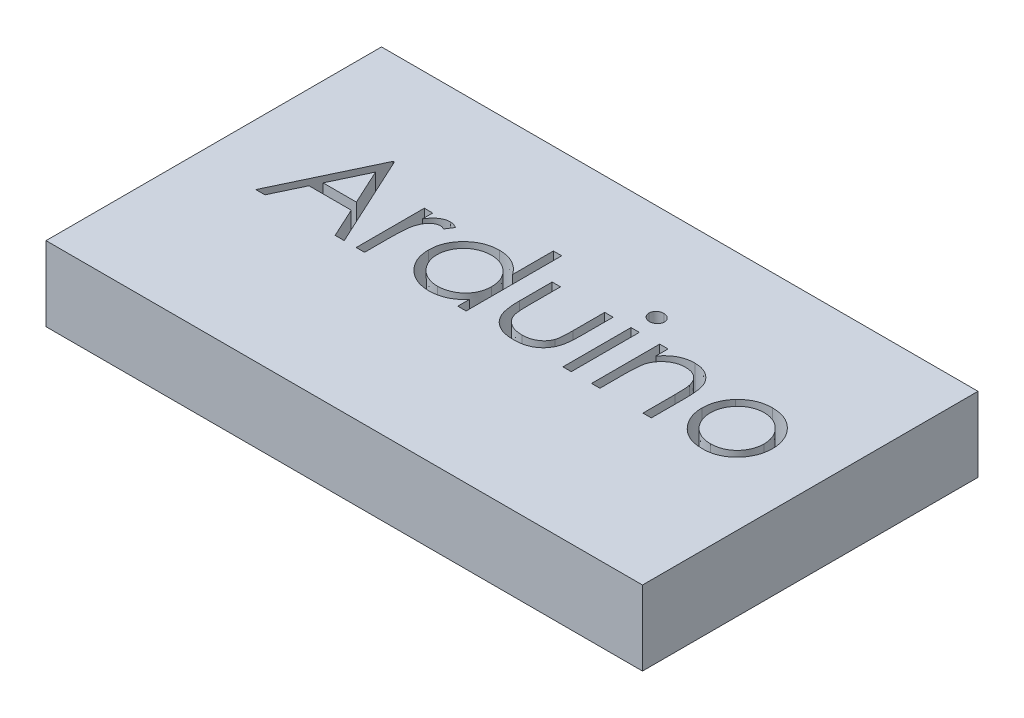
SolidWorks part; units mm, degrees
ref_plane "Front Plane" through (0, 0, 0) normal (0, 0, 1) x (1, 0, 0)
ref_plane "Top Plane" through (0, 0, 0) normal (0, 1, 0) x (1, 0, 0)
ref_plane "Right Plane" through (0, 0, 0) normal (1, 0, 0) x (0, 0, -1)
sketch "Sketch1" plane through (0, 0, 0) normal (0, 1, 0) x (1, 0, 0)
  line L1 (0, 0) -> (101.6, 0)
  line L2 (0, 0) -> (0, 57.15)
  line L3 (0, 57.15) -> (101.6, 57.15)
  line L4 (101.6, 0) -> (101.6, 57.15)
  dimension "D1" = 57.15
  dimension "D2" = 101.6
extrude "Boss-Extrude1" add sketch "Sketch1" along normal blind 12.7
sketch "Sketch2" plane through (0, 12.7, 0) normal (0, 1, 0) x (1, 0, 0)
  line L0 (0, 57.15) -> (0, 0) construction
  line L1 (101.6, 57.15) -> (0, 57.15) construction
  text T0 "Arduino" font "Century Gothic" height in points 60
  dimension "D1" = 9.525
  dimension "D2" = 31.75
extrude "Cut-Extrude1" cut sketch "Sketch2" against normal through all
